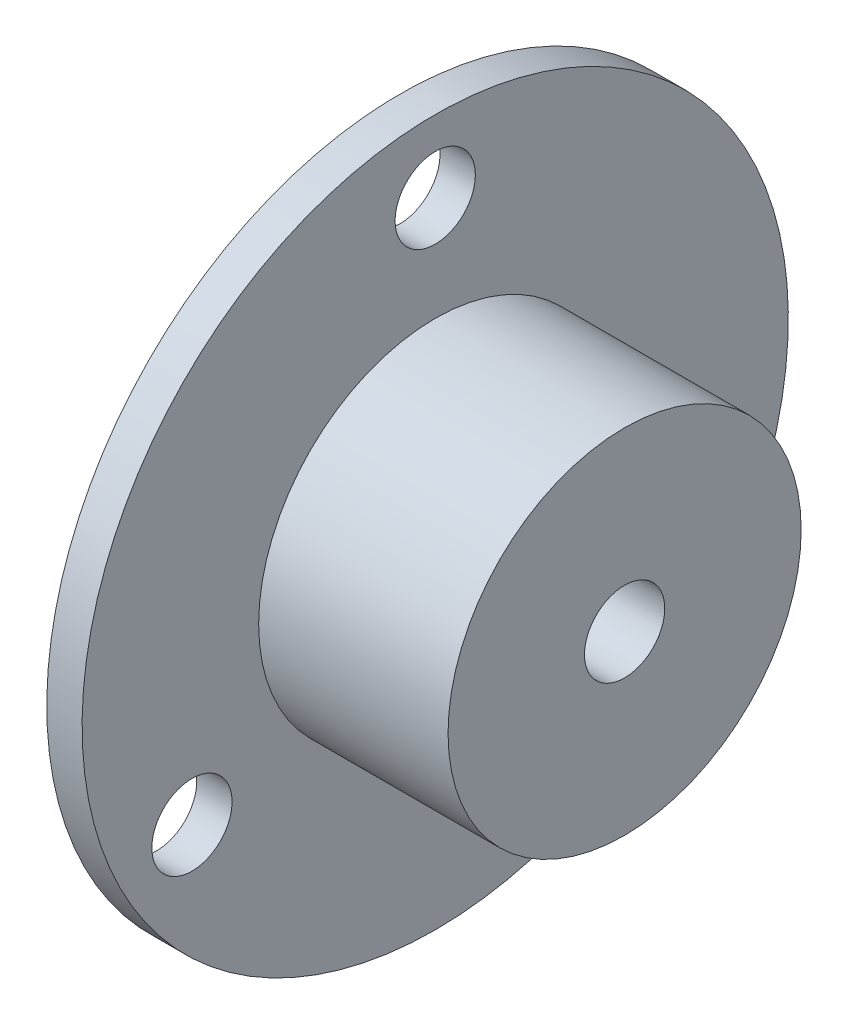
SolidWorks part; units mm, degrees
material "PA 类型 6"
ref_plane "前视基准面" through (0, 0, 0) normal (0, 0, 1) x (1, 0, 0)
ref_plane "上视基准面" through (0, 0, 0) normal (0, 1, 0) x (1, 0, 0)
ref_plane "右视基准面" through (0, 0, 0) normal (1, 0, 0) x (0, 0, -1)
other "Configuration Table"
sketch "草图1" plane through (0, 0, 0) normal (0, 0, 1) x (1, 0, 0)
  line L0 (-10, 0) -> (14, 0)
  line L1 (14, 0) -> (14, -11)
  line L2 (14, -11) -> (2.2, -11)
  line L3 (2.2, -22) -> (0, -22)
  line L4 (0, -22) -> (0, -11)
  line L5 (0, -11) -> (-5, -11)
  line L6 (-5, -11) -> (-5, -4.5)
  line L7 (-5, -4.5) -> (-10, -4.5)
  line L8 (-10, -4.5) -> (-10, 0)
  line L9 (2.2, -11) -> (2.2, -22)
  dimension "D1" = 5
  dimension "D2" = 2.2
  dimension "D3" = 19
  dimension "D4" = 22
  dimension "D5" = 11
  dimension "D6" = 11
  dimension "D7" = 4.5
  dimension "D8" = 5
revolve "旋转1" add sketch "草图1" angle 360 about L0
sketch "草图2" plane through (0, 0, 0) normal (-1, 0, 0) x (0, 0, 1)
  circle A0 centre (0, 0) radius 17.5 construction
  circle A1 centre (0, 17.5) radius 2.5
  circle A2 centre (15.1554, -8.75) radius 2.5
  circle A3 centre (-15.1554, -8.75) radius 2.5
  point P11 (0, 0)
  dimension "D1" = 35
  dimension "D2" = 5
  dimension "D3" = 3
extrude "切除-拉伸1" cut sketch "草图2" against normal blind 10
sketch "草图3" plane through (-10, 0, 0) normal (-1, 0, 0) x (0, 0, 1)
  circle A0 centre (0, 0) radius 2.5
  dimension "D1" = 5
extrude "切除-拉伸2" cut sketch "草图3" against normal through all
